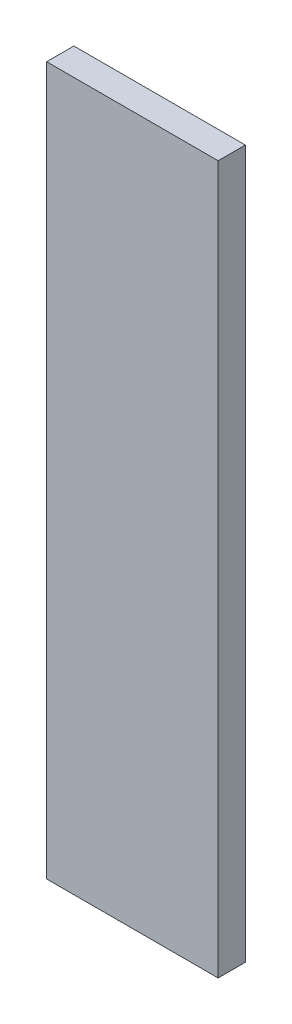
SolidWorks part; units mm, degrees
ref_plane "Front Plane" through (0, 0, 0) normal (0, 0, 1) x (1, 0, 0)
ref_plane "Top Plane" through (0, 0, 0) normal (0, 1, 0) x (1, 0, 0)
ref_plane "Right Plane" through (0, 0, 0) normal (1, 0, 0) x (0, 0, -1)
sketch "Sketch1" plane through (0, 0, 0) normal (0, 0, 1) x (1, 0, 0)
  line L1 (0, 0) -> (16.002, 0)
  line L2 (0, 0) -> (0, 66.04)
  line L3 (0, 66.04) -> (16.002, 66.04)
  line L4 (16.002, 0) -> (16.002, 66.04)
  dimension "D1" = 66.04
  dimension "D2" = 16.002
extrude "Boss-Extrude2" add sketch "Sketch1" along normal blind 2.54
